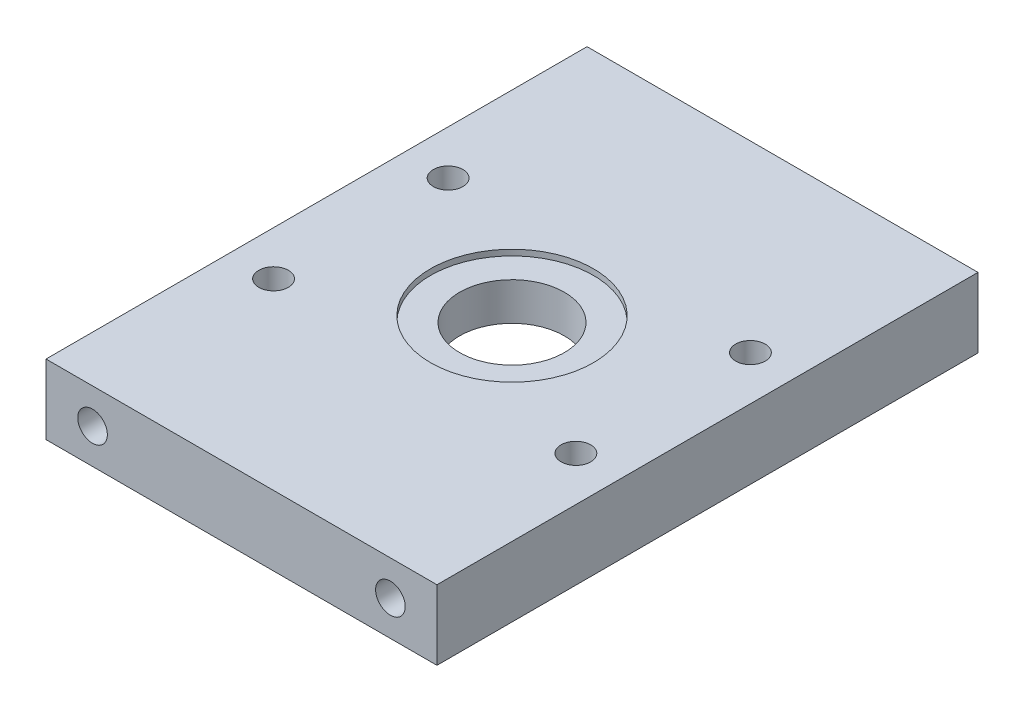
SolidWorks part; units mm, degrees
ref_plane "Front Plane" through (0, 0, 0) normal (0, 0, 1) x (1, 0, 0)
ref_plane "Top Plane" through (0, 0, 0) normal (0, 1, 0) x (1, 0, 0)
ref_plane "Right Plane" through (0, 0, 0) normal (1, 0, 0) x (0, 0, -1)
sketch "Sketch2" plane through (0, 0, 0) normal (0, 1, 0) x (1, 0, 0)
  line L1 (-26.67, -36.9083) -> (26.67, -36.9083)
  line L2 (-26.67, -36.9083) -> (-26.67, 36.9083)
  line L3 (-26.67, 36.9083) -> (26.67, 36.9083)
  line L4 (26.67, -36.9083) -> (26.67, 36.9083)
  line L5 (-26.67, -36.9083) -> (26.67, 36.9083) construction
  line L6 (-26.67, 36.9083) -> (26.67, -36.9083) construction
  circle A0 centre (0, 0) radius 7.1438
  point P0 (0, 0)
  dimension "D3" = 14.2875
  dimension "D1" = 53.34
  dimension "D2" = 73.8167
extrude "Boss-Extrude1" add sketch "Sketch2" along normal blind 9.525
sketch "Sketch3" plane through (0, 9.525, 0) normal (0, 1, 0) x (1, 0, 0)
  circle A0 centre (0, 0) radius 11.1125
  dimension "D1" = 22.225
extrude "Cut-Extrude1" cut sketch "Sketch3" against normal blind 0.7937
sketch "Sketch4" plane through (0, 0, 0) normal (0, -1, 0) x (1, 0, 0)
  circle A0 centre (0, 0) radius 12.7
  dimension "D1" = 25.4
extrude "Cut-Extrude2" cut sketch "Sketch4" against normal blind 3.5719
sketch "Sketch5" plane through (0, 0, 36.9083) normal (0, 0, 1) x (1, 0, 0)
  line L0 (-26.67, 4.7625) -> (26.67, 4.7625)
  line L1 (-26.67, 9.525) -> (-26.67, 0) construction
  line L2 (26.67, 9.525) -> (26.67, 0) construction
  point P6 (-20.32, 4.7625)
  point P7 (20.32, 4.7625)
  dimension "D1" = 6.35
  dimension "D2" = 6.35
hole_wizard "Tap Drill for #10-32 Tap1" positions "Sketch7" profile "Sketch6" hole size "#10-32" standard "ANSI Inch"
sketch "Sketch7" plane through (0, 0, 36.9083) normal (0, 0, 1) x (1, 0, 0)
  point P0 (-20.32, 4.7625)
  point P3 (20.32, 4.7625)
sketch "Sketch6" plane through (-20.32, 4.7625, 36.9083) normal (1, 0, 0) x (0, -1, 0)
  line L0 (0, 0) -> (0, 7.5633)
  line L1 (0, 7.5633) -> (2.0193, 6.35)
  line L2 (2.0193, 6.35) -> (2.0193, 0)
  line L5 (2.0193, 0) -> (0, 0)
  line L10 (0, 7.5633) -> (-2.0193, 6.35) construction
  line L11 (0, -6.35) -> (0, 107.95) construction
  dimension "Hole Dia." = 4.0386
  dimension "Hole Depth" = 6.35
  dimension "Drill Angle" = 118
mirror "Mirror1" about plane through (0, 0, 0) normal (0, 0, 1) of "Tap Drill for #10-32 Tap1"
sketch "Sketch8" plane through (0, 9.525, 0) normal (0, 1, 0) x (1, 0, 0)
  circle A0 centre (0, 0) radius 23.8125
  point P3 (0, -23.8125)
  point P4 (-20.6222, -11.9063)
  point P7 (-20.6222, 11.9062)
  point P8 (0, 23.8125)
  point P9 (20.6222, 11.9063)
  point P10 (20.6222, -11.9063)
  point P11 (0, 0)
  dimension "D1" = 47.625
  dimension "D2" = 6
hole_wizard "Tap Drill for #10-32 Tap2" positions "Sketch10" profile "Sketch9" hole size "#10-32" standard "ANSI Inch" end condition through all
sketch "Sketch10" plane through (0, 9.525, 0) normal (0, 1, 0) x (1, 0, 0)
  point P0 (-20.6222, 11.9062)
  point P3 (-20.6222, -11.9063)
  point P6 (20.6222, -11.9063)
  point P9 (20.6222, 11.9063)
sketch "Sketch9" plane through (-20.6222, 9.525, -11.9062) normal (1, 0, 0) x (0, 0, 1)
  line L0 (0, 0) -> (0, 9.525)
  line L1 (0, 9.525) -> (2.0193, 9.525)
  line L2 (2.0193, 9.525) -> (2.0193, 0)
  line L5 (2.0193, 0) -> (0, 0)
  line L11 (0, -6.35) -> (0, 107.95) construction
  dimension "Thru Hole Dia." = 4.0386
  dimension "Thru Hole Depth" = 9.525
